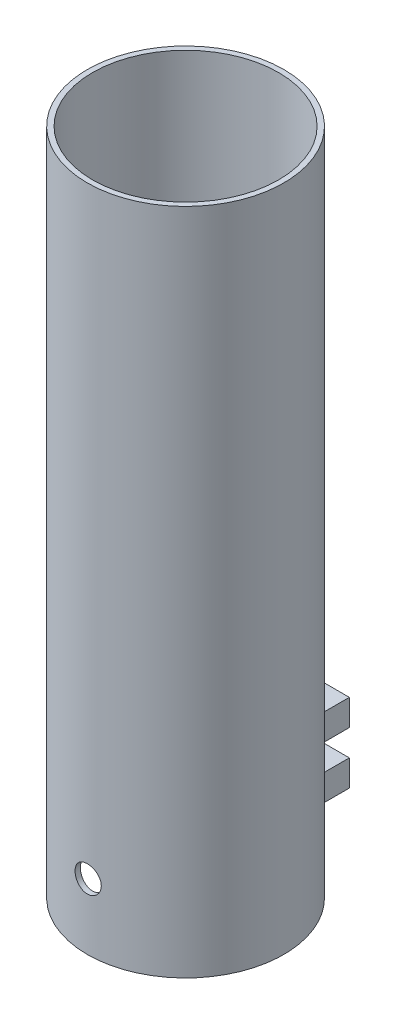
SolidWorks part; units mm, degrees
ref_plane "Front Plane" through (0, 0, 0) normal (0, 0, 1) x (1, 0, 0)
ref_plane "Top Plane" through (0, 0, 0) normal (0, 1, 0) x (1, 0, 0)
ref_plane "Right Plane" through (0, 0, 0) normal (1, 0, 0) x (0, 0, -1)
sketch "Sketch1" plane through (0, 0, 0) normal (0, 1, 0) x (1, 0, 0)
  circle A0 centre (0, 0) radius 37.5
  circle A1 centre (0, 0) radius 35.5
  dimension "D1" = 75
  dimension "D2" = 71
extrude "Boss-Extrude1" add sketch "Sketch1" along normal blind 255
sketch "Sketch2" plane through (0, 0, 0) normal (0, 0, 1) x (1, 0, 0)
  circle A0 centre (0, 25) radius 5
  dimension "D1" = 10
  dimension "D2" = 25
extrude "Cut-Extrude1" cut sketch "Sketch2" against normal through all both and the other way through all
ref_plane "Plane1" through (0, 0, -37.5) normal (0, 0, -1) x (-1, 0, 0)
sketch "Sketch3" plane through (0, 0, -37.5) normal (0, 0, -1) x (-1, 0, 0)
  line L0 (0, 43.0165) -> (0, 3.3239) construction
  line L1 (-5, 30) -> (5, 30)
  line L2 (-5, 30) -> (-5, 40)
  line L3 (-5, 40) -> (5, 40)
  line L4 (5, 30) -> (5, 40)
  line L5 (-5, 30) -> (5, 40) construction
  line L6 (-5, 40) -> (5, 30) construction
  line L7 (-5, 10) -> (5, 10)
  line L8 (-5, 10) -> (-5, 20)
  line L9 (-5, 20) -> (5, 20)
  line L10 (5, 10) -> (5, 20)
  line L11 (-5, 10) -> (5, 20) construction
  line L12 (-5, 20) -> (5, 10) construction
  circle A0 centre (0, 25) radius 5 construction
  point P0 (0, 35)
  point P5 (0, 15)
  dimension "D1" = 10
  dimension "D2" = 10
  dimension "D3" = 5
  dimension "D4" = 5
extrude "Boss-Extrude2" add sketch "Sketch3" along normal blind 20 separate body
